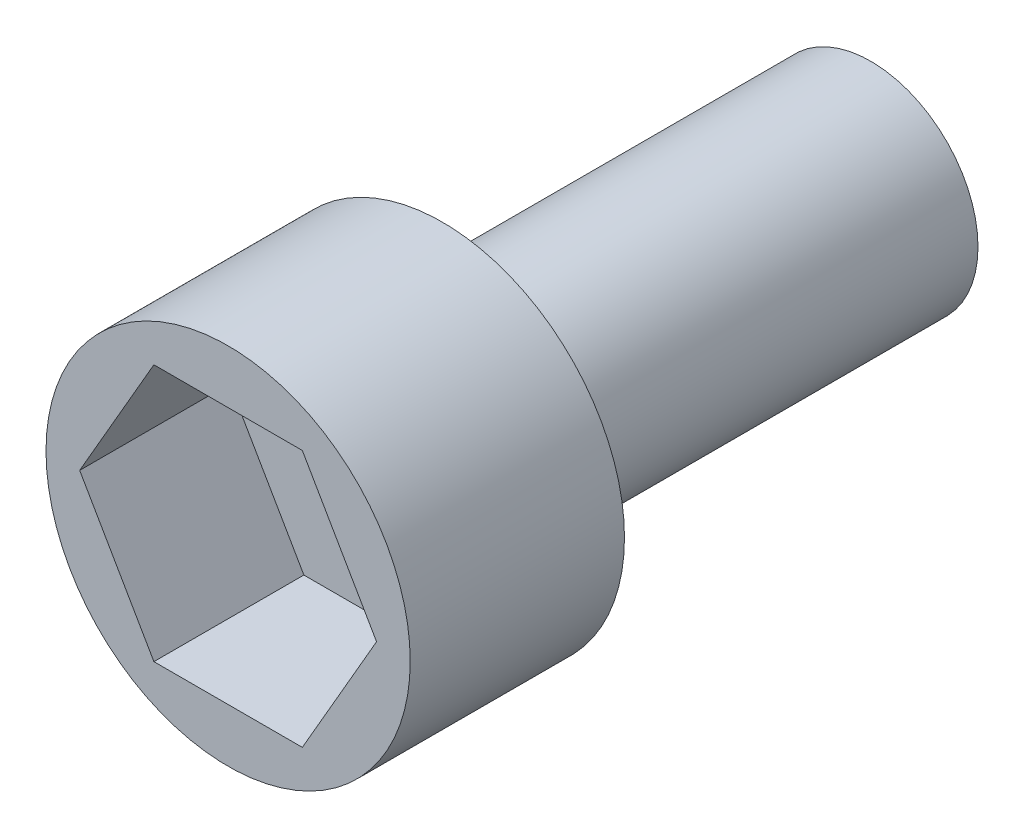
SolidWorks part; units mm, degrees
ref_plane "Plan de face" through (0, 0, 0) normal (0, 0, 1) x (1, 0, 0)
ref_plane "Plan de dessus" through (0, 0, 0) normal (0, 1, 0) x (1, 0, 0)
ref_plane "Plan de droite" through (0, 0, 0) normal (1, 0, 0) x (0, 0, -1)
sketch "Esquisse1" plane through (0, 0, 0) normal (0, 0, 1) x (1, 0, 0)
  circle A0 centre (0, 0) radius 2.5
  dimension "D1" = 5
extrude "Boss.-Extru.1" add sketch "Esquisse1" along normal blind 10
sketch "Esquisse2" plane through (0, 0, 10) normal (0, 0, 1) x (1, 0, 0)
  circle A0 centre (0, 0) radius 4.25
  dimension "D1" = 8.5
extrude "Boss.-Extru.2" add sketch "Esquisse2" along normal blind 5
sketch "Esquisse3" plane through (0, 0, 15) normal (0, 0, 1) x (1, 0, 0)
  line L1 (3.4641, 0) -> (1.7321, 3)
  line L2 (1.7321, 3) -> (-1.7321, 3)
  line L3 (-1.7321, 3) -> (-3.4641, 0)
  line L4 (-3.4641, 0) -> (-1.7321, -3)
  line L5 (-1.7321, -3) -> (1.7321, -3)
  line L6 (1.7321, -3) -> (3.4641, 0)
  circle A0 centre (0, 0) radius 3 construction
  dimension "D1" = 6
extrude "Enlèv. mat.-Extru.1" cut sketch "Esquisse3" against normal blind 3.5
